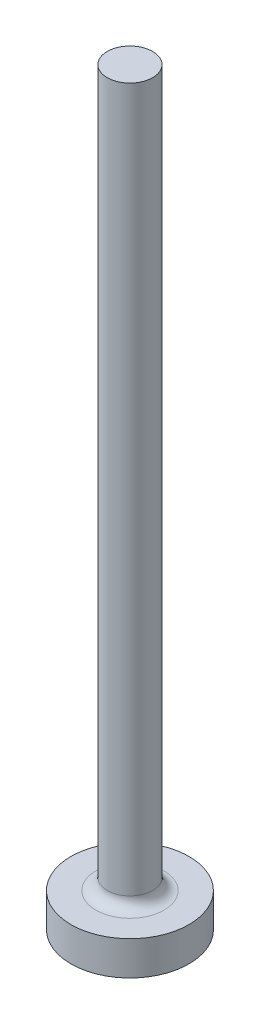
SolidWorks part; units mm, degrees
ref_plane "Front Plane" through (0, 0, 0) normal (0, 0, 1) x (1, 0, 0)
ref_plane "Top Plane" through (0, 0, 0) normal (0, 1, 0) x (1, 0, 0)
ref_plane "Right Plane" through (0, 0, 0) normal (1, 0, 0) x (0, 0, -1)
sketch "Sketch1" plane through (0, 0, 0) normal (0, 1, 0) x (1, 0, 0)
  circle A0 centre (0, 0) radius 2.6
  dimension "D1" = 5.2
extrude "Boss-Extrude1" add sketch "Sketch1" along normal blind 1.5
sketch "Sketch2" plane through (0, 1.5, 0) normal (0, 1, 0) x (1, 0, 0)
  circle A0 centre (0, 0) radius 1
  dimension "D1" = 2
extrude "Boss-Extrude2" add sketch "Sketch2" along normal blind 31.5
fillet "Fillet1" radius 0.5 1 edges at (0, 1.5, 1)
equation "\"D1@Sketch1\"=5.2"
